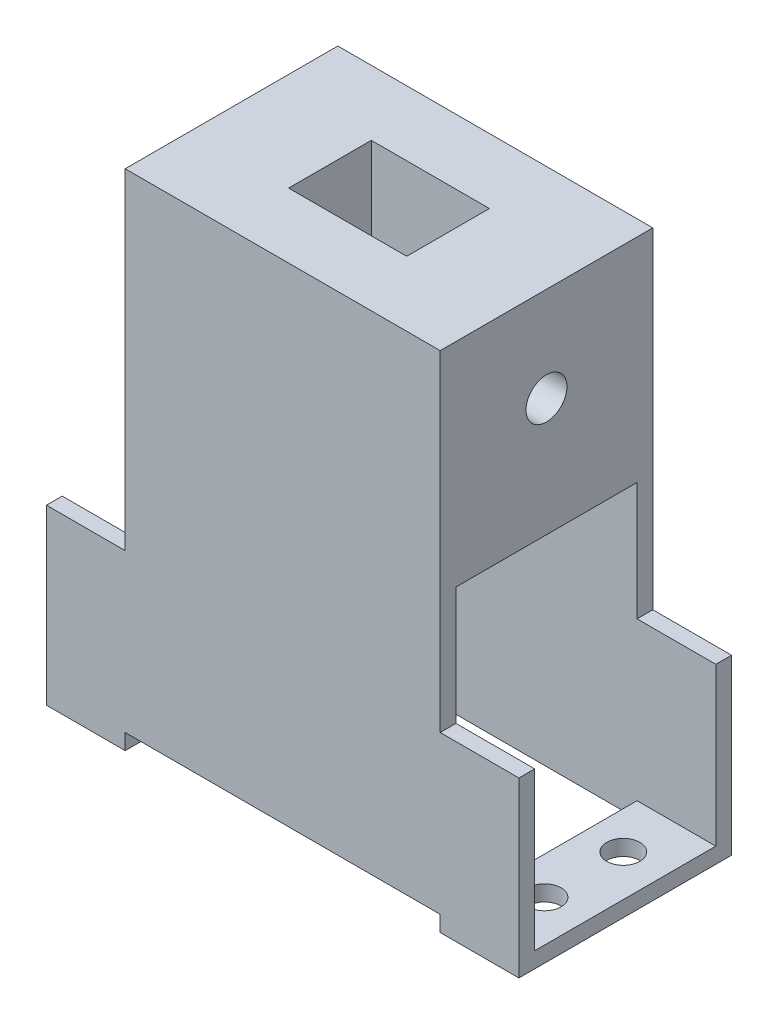
SolidWorks part; units mm, degrees
ref_plane "前视基准面" through (0, 0, 0) normal (0, 0, 1) x (1, 0, 0)
ref_plane "上视基准面" through (0, 0, 0) normal (0, 1, 0) x (1, 0, 0)
ref_plane "右视基准面" through (0, 0, 0) normal (1, 0, 0) x (0, 0, -1)
sketch "草图1" plane through (0, 0, 0) normal (0, 0, 1) x (1, 0, 0)
  line L0 (20, 2.5) -> (30, 2.5)
  line L1 (-20, -17.5) -> (20, -17.5)
  line L2 (-20, -17.5) -> (-20, 17.5)
  line L3 (-20, 17.5) -> (20, 17.5)
  line L4 (20, -17.5) -> (20, 17.5)
  line L5 (-20, -17.5) -> (20, 17.5) construction
  line L6 (-20, 17.5) -> (20, -17.5) construction
  line L7 (30, 2.5) -> (30, -17.5)
  line L8 (30, -17.5) -> (20, -17.5)
  line L9 (-20, -17.5) -> (-30, -17.5)
  line L10 (-30, -17.5) -> (-30, 2.5)
  line L11 (-30, 2.5) -> (-20, 2.5)
  line L12 (-30, -17.5) -> (-20, -17.5)
  point P0 (0, 0)
  dimension "D1" = 40
  dimension "D2" = 35
  dimension "D3" = 10
  dimension "D4" = 10
  dimension "D5" = 20
  dimension "D6" = 20
extrude "凸台-拉伸1" add sketch "草图1" along normal blind 2 contours L11 L10 L9 L2 | L1 L4 L3 L2 | L8 L7 L0 L4
sketch "草图3" plane through (0, -17.5, 0) normal (0, -1, 0) x (1, 0, 0)
  line L0 (-30, 2) -> (-30, -23)
  line L2 (-20, -23) -> (-20, 2)
  line L3 (30, 2) -> (-30, 2) construction
  line L4 (-20, 2) -> (-30, 2)
  line L5 (30, -23) -> (30, 2)
  line L6 (30, 2) -> (20, 2)
  line L7 (20, 2) -> (20, -23)
  line L10 (-30, -23) -> (-20, -23)
  line L11 (20, -23) -> (30, -23)
  dimension "D1" = 10
  dimension "D2" = 25
  dimension "D3" = 10
extrude "凸台-拉伸2" add sketch "草图3" along normal blind 2
sketch "草图4" plane through (0, 0, -23) normal (0, 0, -1) x (-1, 0, 0)
  line L0 (30, -19.5) -> (30, -17.5) construction
  line L1 (-30, -19.5) -> (-30, -17.5) construction
  line L2 (30, -19.5) -> (30, -17.5)
  line L3 (-30, -19.5) -> (-30, -17.5)
  line L4 (-30, -19.5) -> (30, -19.5)
  line L10 (30, 2.5) -> (20, 2.5)
  line L11 (20, 2.5) -> (20, 17.5)
  line L12 (20, 17.5) -> (-20, 17.5)
  line L13 (-20, 17.5) -> (-20, 2.5)
  line L14 (-20, 2.5) -> (-30, 2.5)
  line L15 (-30, 2.5) -> (-30, -17.5)
  line L16 (-30, -17.5) -> (-20, -17.5)
  line L17 (-20, -17.5) -> (20, -17.5)
  line L18 (20, -17.5) -> (30, -17.5)
  line L19 (30, -17.5) -> (30, 2.5)
  line L20 (30, 2.5) -> (20, 2.5)
  line L21 (20, 2.5) -> (20, 17.5)
  line L22 (20, 17.5) -> (-20, 17.5)
  line L23 (-20, 17.5) -> (-20, 2.5)
  line L24 (-20, 2.5) -> (-30, 2.5)
  line L25 (-30, 2.5) -> (-30, -17.5)
  line L29 (30, -17.5) -> (30, 2.5)
  dimension "D1" = 0
extrude "凸台-拉伸3" add sketch "草图4" along normal blind 2
sketch "草图5" plane through (0, -17.5, 0) normal (0, 1, 0) x (1, 0, 0)
  line L0 (20, 0) -> (20, 23) construction
  line L1 (20, -2) -> (20, 23) construction
  line L2 (-20, 23) -> (-20, -2) construction
  line L3 (30, 11.5) -> (-30, 11.5) construction
  line L4 (30, 23) -> (30, 0) construction
  line L5 (-30, 0) -> (-30, 23) construction
  circle A0 centre (24.75, 16.5) radius 2.1
  circle A1 centre (24.75, 6.5) radius 2.1
  circle A2 centre (-24.75, 16.5) radius 2.1
  circle A3 centre (-24.75, 6.5) radius 2.1
  dimension "D2" = 4.2
  dimension "D3" = 4.2
  dimension "D7" = 4.2
  dimension "D8" = 4.2
  dimension "D1" = 4.75
  dimension "D4" = 4.75
  dimension "D5" = 4.75
  dimension "D6" = 4.75
  dimension "D9" = 5
  dimension "D10" = 5
  dimension "D11" = 5
  dimension "D12" = 5
extrude "切除-拉伸1" cut sketch "草图5" against normal up to next
sketch "草图6" plane through (0, 17.5, 0) normal (0, 1, 0) x (1, 0, 0)
  line L1 (-20, 0) -> (-20, -2) construction
  line L2 (-20, -2) -> (20, -2) construction
  line L3 (20, -2) -> (20, 0) construction
  line L5 (20, 23) -> (20, 25) construction
  line L6 (20, 25) -> (-20, 25) construction
  line L7 (-20, 25) -> (-20, 23) construction
  line L9 (-20, 0) -> (-20, -2)
  line L10 (-20, -2) -> (20, -2)
  line L11 (20, -2) -> (20, 0)
  line L13 (20, 23) -> (20, 25)
  line L14 (20, 25) -> (-20, 25)
  line L15 (-20, 25) -> (-20, 23)
  line L16 (-20, 23) -> (-20, 0)
  line L17 (20, 23) -> (20, 0)
extrude "凸台-拉伸5" add sketch "草图6" along normal blind 2
sketch "草图7" plane through (0, 19.5, 0) normal (0, 1, 0) x (1, 0, 0)
  line L4 (20, -2) -> (20, 25)
  line L5 (20, 25) -> (-20, 25)
  line L6 (-20, 25) -> (-20, -2)
  line L7 (-20, -2) -> (20, -2)
  line L8 (20, -2) -> (20, 25)
  line L9 (20, 25) -> (-20, 25)
  line L10 (-20, 25) -> (-20, -2)
  line L11 (-20, -2) -> (20, -2)
  dimension "D1" = 0
extrude "凸台-拉伸6" add sketch "草图7" along normal blind 25
sketch "草图8" plane through (-20, 0, 0) normal (-1, 0, 0) x (0, 0, 1)
  line L0 (-11.5, 44.5) -> (-11.5, 17.5) construction
  line L1 (-25, 44.5) -> (2, 44.5) construction
  line L2 (-23, 17.5) -> (0, 17.5) construction
  circle A0 centre (-11.5, 32.5) radius 2.6
  dimension "D1" = 5.2
  dimension "D2" = 15
extrude "切除-拉伸2" cut sketch "草图8" against normal up to next
sketch "草图9" plane through (0, 44.5, 0) normal (0, 1, 0) x (1, 0, 0)
  line L0 (-20, 11.5) -> (20, 11.5) construction
  line L1 (-7.5, 6.25) -> (7.5, 6.25)
  line L2 (-7.5, 6.25) -> (-7.5, 16.75)
  line L3 (-7.5, 16.75) -> (7.5, 16.75)
  line L4 (7.5, 6.25) -> (7.5, 16.75)
  line L5 (-7.5, 6.25) -> (7.5, 16.75) construction
  line L6 (-7.5, 16.75) -> (7.5, 6.25) construction
  line L7 (-20, 25) -> (-20, -2) construction
  line L8 (20, -2) -> (20, 25) construction
  line L9 (0, -2) -> (0, 25) construction
  line L10 (-20, -2) -> (20, -2) construction
  line L11 (20, 25) -> (-20, 25) construction
  point P0 (0, 11.5)
  point P17 (0, 11.5)
  dimension "D1" = 10.5
  dimension "D2" = 15
extrude "切除-拉伸3" cut sketch "草图9" against normal blind 22.2
